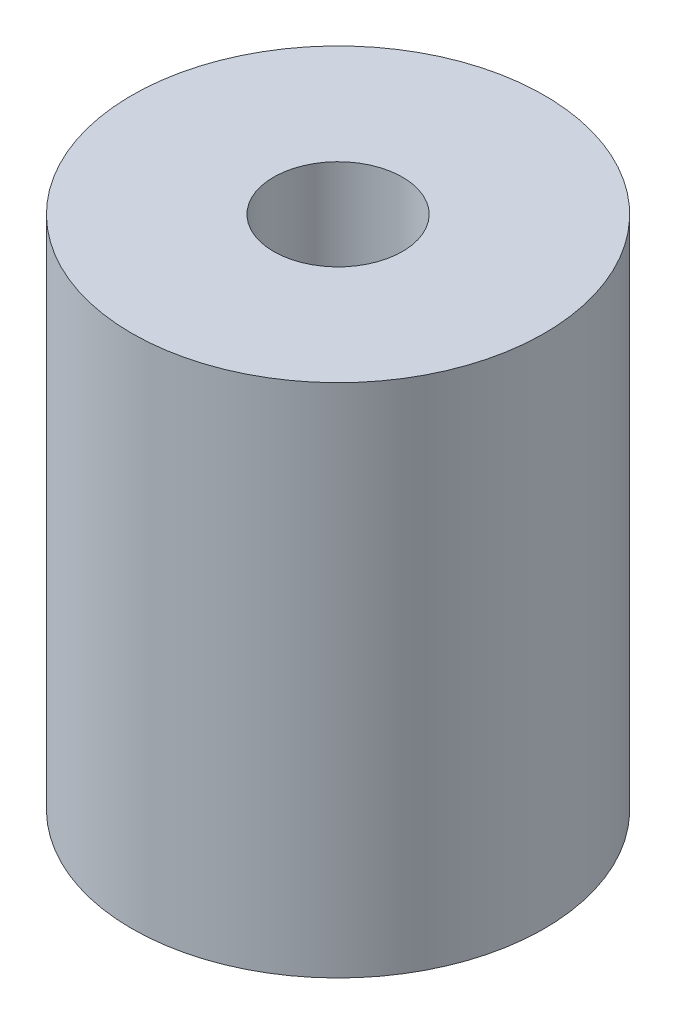
SolidWorks part; units mm, degrees
ref_plane "Спереди" through (0, 0, 0) normal (0, 0, 1) x (1, 0, 0)
ref_plane "Сверху" through (0, 0, 0) normal (0, 1, 0) x (1, 0, 0)
ref_plane "Справа" through (0, 0, 0) normal (1, 0, 0) x (0, 0, -1)
sketch "Эскиз1" plane through (0, 0, 0) normal (0, 1, 0) x (1, 0, 0)
  circle A0 centre (0, 0) radius 4
  circle A1 centre (0, 0) radius 1.25
  dimension "D1" = 2.5
  dimension "D2" = 8
extrude "Бобышка-Вытянуть1" add sketch "Эскиз1" along normal blind 10
